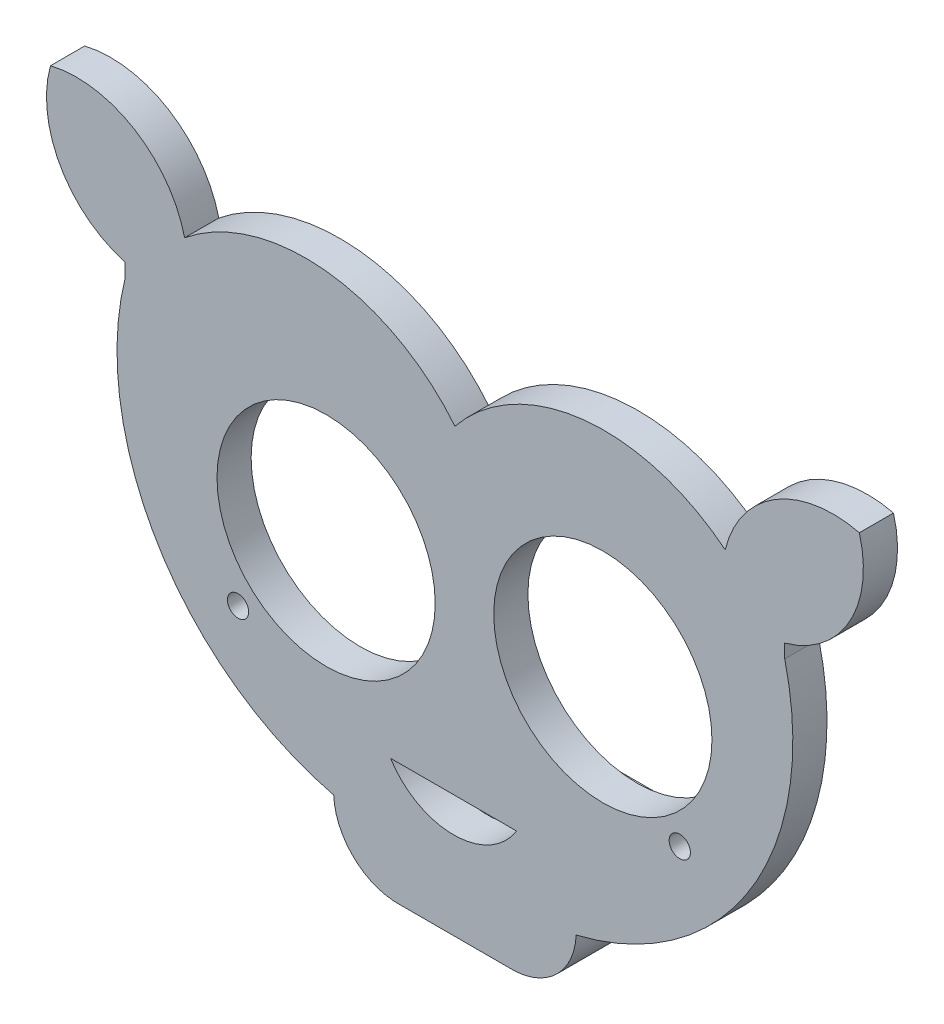
SolidWorks part; units mm, degrees
ref_plane "Front Plane" through (0, 0, 0) normal (0, 0, 1) x (1, 0, 0)
ref_plane "Top Plane" through (0, 0, 0) normal (0, 1, 0) x (1, 0, 0)
ref_plane "Right Plane" through (0, 0, 0) normal (1, 0, 0) x (0, 0, -1)
sketch "Sketch2" plane through (0, 0, 0) normal (0, 0, 1) x (1, 0, 0)
  line L2 (29.3951, -26.1665) -> (19.286, -26.1665)
  arc A0 (12.9522, -20.3592) -> (-6.643, 11.9036) centre (19.286, 5.5698) cw
  arc A1 (12.9522, -20.3592) -> (19.286, -26.1665) centre (19.0228, -20.0959) ccw
  arc A2 (-6.643, 13.1941) -> (-13.6543, 25.6782) centre (-3.9066, 22.9419) cw
  arc A3 (-13.6543, 25.6782) -> (-1.0503, 17.9841) centre (-11.1994, 15.5291) cw
  arc A4 (-1.0503, 17.9841) -> (24.3406, 15.345) centre (10.3256, 3.9691) cw
  arc A5 (49.7314, 17.9841) -> (24.3406, 15.345) centre (38.3556, 3.9691) ccw
  arc A6 (62.3355, 25.6782) -> (49.7314, 17.9841) centre (59.8805, 15.5291) ccw
  arc A7 (55.3241, 13.1941) -> (62.3355, 25.6782) centre (52.5878, 22.9419) ccw
  arc A8 (35.7289, -20.3592) -> (29.3951, -26.1665) centre (29.6584, -20.0959) cw
  arc A9 (35.7289, -20.3592) -> (55.3241, 11.9036) centre (29.3951, 5.5698) ccw
  spline S0 degree 1 poles (-6.643, 13.1941) (-6.643, 11.9036) knots 0 0 1 1
  spline S1 degree 1 poles (55.3241, 13.1941) (55.3241, 11.9036) knots 0 0 1 1
extrude "Boss-Extrude2" add sketch "Sketch2" along normal blind 15
sketch "Sketch4" plane through (0, 0, 0) normal (0, 0, 1) x (1, 0, 0)
  line L0 (18.2914, -14.6924) -> (30.1446, -14.6924)
  circle A0 centre (12.2375, 0) radius 10.25
  circle A1 centre (38.2375, 1.9022) radius 10.25
  arc A2 (18.2914, -14.6924) -> (30.1446, -14.6924) centre (24.218, -10.9627) ccw
  dimension "D1" = 20.5
  dimension "D2" = 20.5
  dimension "D3" = 26
extrude "Cut-Extrude1" cut sketch "Sketch4" along normal blind 39
sketch "Sketch5" plane through (0, 0, 0) normal (0, 0, 1) x (1, 0, 0)
  circle A0 centre (3.9663, -9.4606) radius 1
  circle A1 centre (45.4663, -8.2816) radius 1
  dimension "D1" = 2
  dimension "D2" = 2
  dimension "D3" = 41.5
extrude "Cut-Extrude2" cut sketch "Sketch5" along normal blind 46
sketch "Sketch8" plane through (0, 0, 0) normal (0, 1, 0) x (1, 0, 0)
  line L1 (-19.2303, 0) -> (68.0749, 0)
  line L2 (-19.2303, 0) -> (-19.2303, -11.7917)
  line L3 (-19.2303, -11.7917) -> (68.0749, -11.7917)
  line L4 (68.0749, 0) -> (68.0749, -11.7917)
extrude "Cut-Extrude4" cut sketch "Sketch8" along normal blind 30 and the other way blind 20
sketch "Sketch9" plane through (0, 0, 0) normal (0, 1, 0) x (1, 0, 0)
  circle A0 centre (24.8311, -5.8242) radius 1.5
  point P2 (24.8311, -5.8242)
  dimension "D1" = 3
extrude "Cut-Extrude5" cut sketch "Sketch9" against normal blind 45
